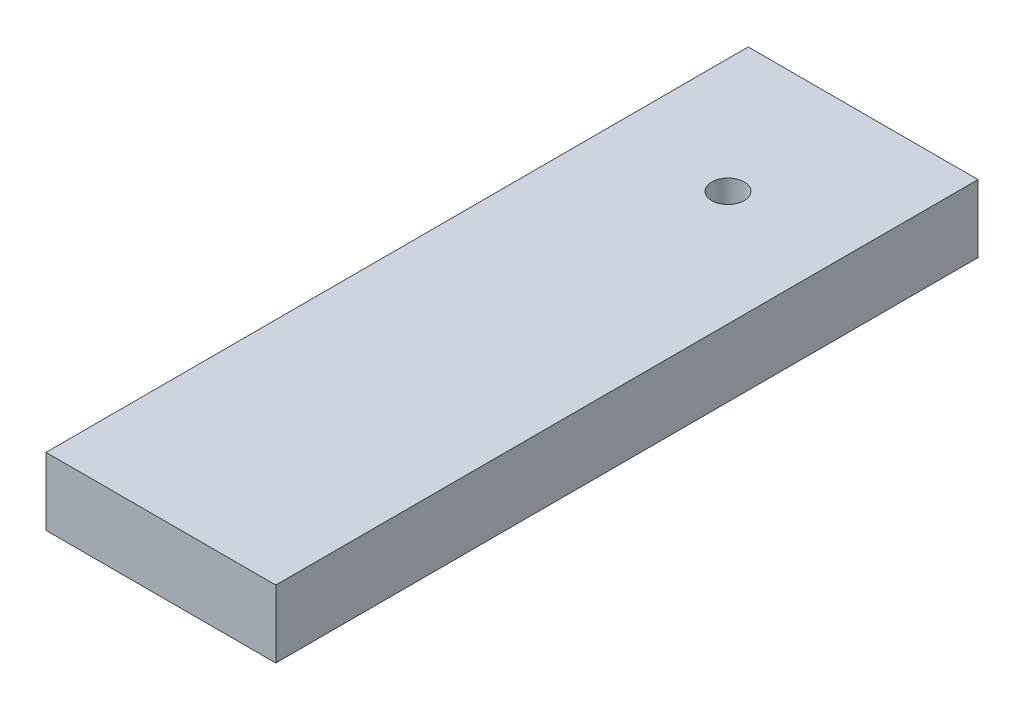
SolidWorks part; units mm, degrees
ref_plane "Front Plane" through (0, 0, 0) normal (0, 0, 1) x (1, 0, 0)
ref_plane "Top Plane" through (0, 0, 0) normal (0, 1, 0) x (1, 0, 0)
ref_plane "Right Plane" through (0, 0, 0) normal (1, 0, 0) x (0, 0, -1)
sketch "Sketch1" plane through (0, 0, 0) normal (0, 1, 0) x (1, 0, 0)
  line L1 (-10.795, 40.8361) -> (10.795, 40.8361)
  line L2 (-10.795, 40.8361) -> (-10.795, -40.8361)
  line L3 (-10.795, -40.8361) -> (10.795, -40.8361)
  line L4 (10.795, 40.8361) -> (10.795, -40.8361)
  line L5 (-10.795, 40.8361) -> (10.795, -40.8361) construction
  line L6 (-10.795, -40.8361) -> (10.795, 40.8361) construction
  line L7 (-10.668, 40.8361) -> (10.668, 40.8361) construction
  point P0 (0, 0)
  dimension "D1" = 21.59
extrude "Boss-Extrude1" add sketch "Sketch1" along normal blind 6.35
sketch "Sketch2" plane through (0, 6.35, 0) normal (0, 1, 0) x (1, 0, 0)
  line L0 (-10.795, 40.8361) -> (-10.795, -40.8361) construction
  line L1 (10.795, -40.8361) -> (-10.795, -40.8361)
  line L2 (10.795, -40.8361) -> (10.795, -25.15)
  line L3 (10.795, -25.15) -> (-10.795, -25.15)
  line L4 (-10.795, -40.8361) -> (-10.795, -25.15)
extrude "Cut-Extrude1" cut sketch "Sketch2" against normal up to surface (6.35 mm away) up to face at (0, 0, 0)
sketch "Sketch3" plane through (0, 6.35, 0) normal (0, 1, 0) x (1, 0, 0)
  circle A0 centre (0, 28.1361) radius 1.524
  dimension "D1" = 3.048
extrude "Cut-Extrude2" cut sketch "Sketch3" against normal up to surface (6.35 mm away) up to face at (0, 0, -7.8431)
